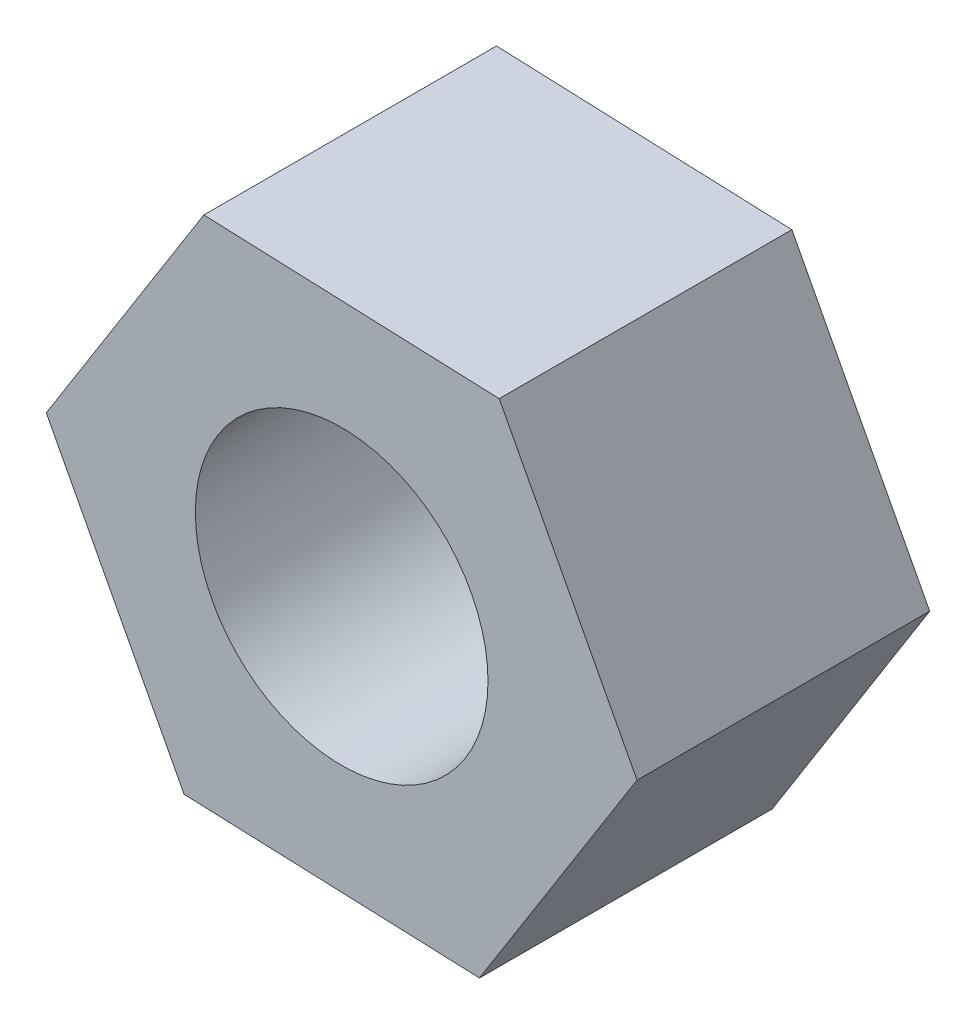
SolidWorks part; units mm, degrees
ref_plane "Front Plane" through (0, 0, 0) normal (0, 0, 1) x (1, 0, 0)
ref_plane "Top Plane" through (0, 0, 0) normal (0, 1, 0) x (1, 0, 0)
ref_plane "Right Plane" through (0, 0, 0) normal (1, 0, 0) x (0, 0, -1)
sketch "Sketch1" plane through (0, 0, 0) normal (0, 0, 1) x (1, 0, 0)
  line L0 (-2.1533, -3.4183) -> (1.8837, -3.574)
  line L1 (1.8837, -3.574) -> (4.037, -0.1557)
  line L2 (4.037, -0.1557) -> (2.1533, 3.4183)
  line L3 (2.1533, 3.4183) -> (-1.8837, 3.574)
  line L4 (-1.8837, 3.574) -> (-4.037, 0.1557)
  line L5 (-4.037, 0.1557) -> (-2.1533, -3.4183)
  circle A0 centre (0, 0) radius 3.4987 construction
  circle A1 centre (0, 0) radius 2
  dimension "D3" = 4
  dimension "D1" = 4.04
  dimension "D2" = 4.037
extrude "Boss-Extrude1" add sketch "Sketch1" along normal blind 4
